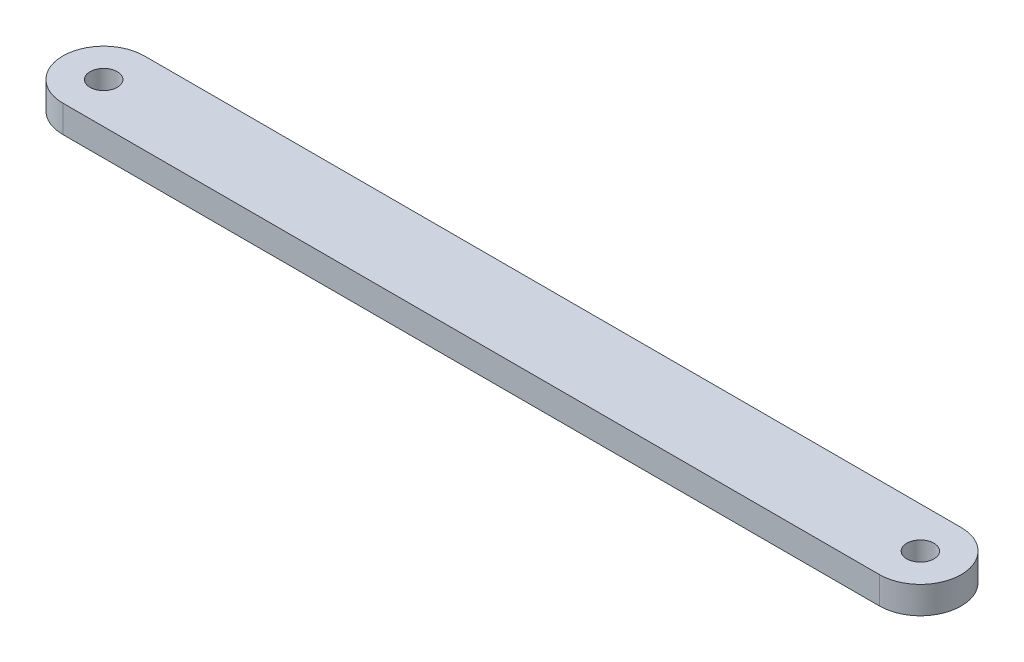
SolidWorks part; units mm, degrees
ref_plane "Front Plane" through (0, 0, 0) normal (0, 0, 1) x (1, 0, 0)
ref_plane "Top Plane" through (0, 0, 0) normal (0, 1, 0) x (1, 0, 0)
ref_plane "Right Plane" through (0, 0, 0) normal (1, 0, 0) x (0, 0, -1)
sketch "Sketch1" plane through (0, 0, 0) normal (0, 1, 0) x (1, 0, 0)
  line L1 (-75, 7.5) -> (75, 7.5)
  line L3 (-75, -7.5) -> (75, -7.5)
  line L5 (-75, 7.5) -> (75, -7.5) construction
  line L6 (-75, -7.5) -> (75, 7.5) construction
  arc A0 (75, 7.5) -> (75, -7.5) centre (75, 0) cw
  arc A1 (-75, 7.5) -> (-75, -7.5) centre (-75, 0) ccw
  circle A2 centre (-75, 0) radius 2.5
  circle A3 centre (75, 0) radius 2.5
  point P0 (0, 0)
  dimension "D3" = 5
  dimension "D4" = 5
  dimension "D1" = 150
  dimension "D2" = 15
extrude "Boss-Extrude1" add sketch "Sketch1" along normal blind 5
